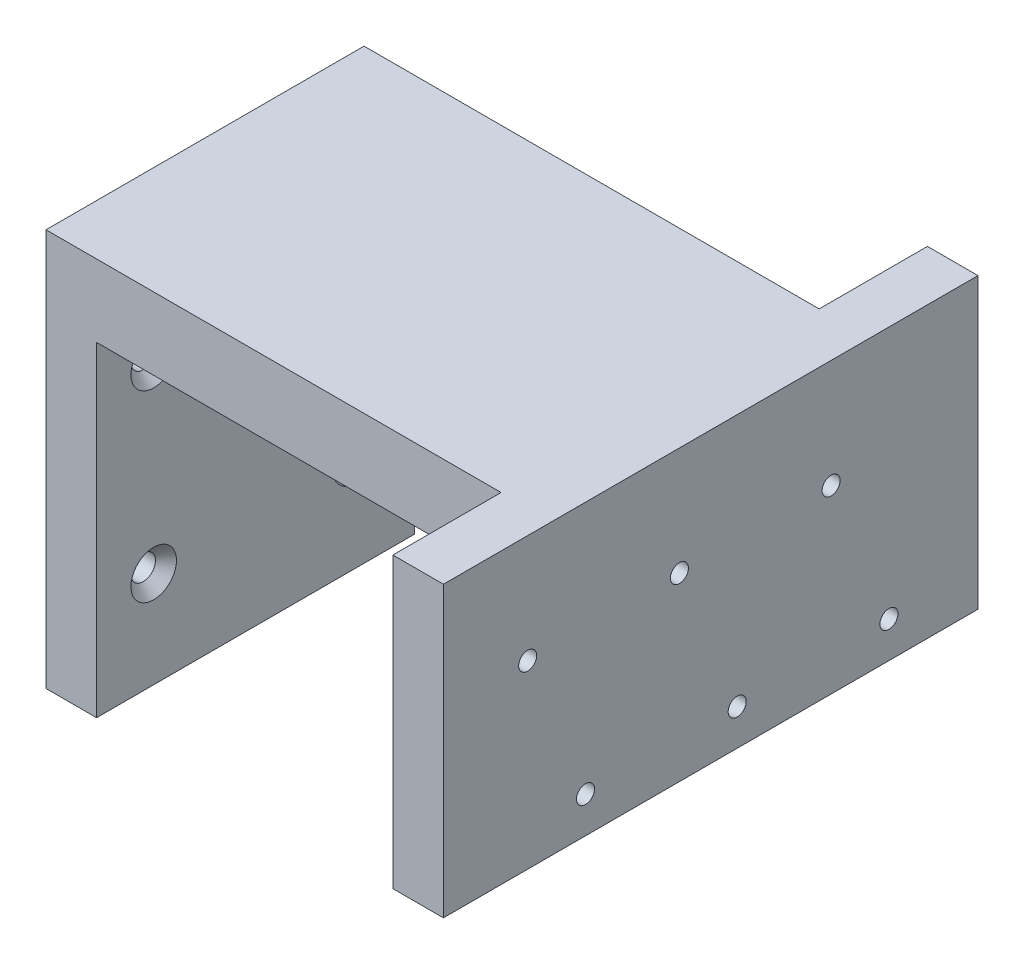
SolidWorks part; units mm, degrees
ref_plane "Front Plane" through (0, 0, 0) normal (0, 0, 1) x (1, 0, 0)
ref_plane "Top Plane" through (0, 0, 0) normal (0, 1, 0) x (1, 0, 0)
ref_plane "Right Plane" through (0, 0, 0) normal (1, 0, 0) x (0, 0, -1)
sketch "Sketch1" plane through (0, 0, 0) normal (0, 0, 1) x (1, 0, 0)
  line L1 (0, 0) -> (70, 0)
  line L2 (0, 0) -> (0, 55)
  line L3 (0, 55) -> (70, 55)
  line L4 (70, 0) -> (70, 55)
  dimension "D1" = 70
  dimension "D2" = 55
extrude "Boss-Extrude1" add sketch "Sketch1" along normal blind 74
sketch "Sketch2" plane through (0, 0, 74) normal (0, 0, 1) x (1, 0, 0)
  line L0 (7, 0) -> (7, 45)
  line L1 (0, 0) -> (70, 0) construction
  line L2 (7, 45) -> (63, 45)
  line L3 (63, 45) -> (63, 15)
  line L4 (60, 0) -> (7, 0)
  line L5 (0, 55) -> (0, 0) construction
  line L6 (70, 0) -> (70, 55) construction
  line L7 (70, 55) -> (0, 55) construction
  line L8 (63, 15) -> (70, 15)
  line L9 (70, 15) -> (70, 0)
  line L10 (70, 0) -> (60, 0)
  dimension "D1" = 7
  dimension "D2" = 7
  dimension "D3" = 10
  dimension "D4" = 15
extrude "Cut-Extrude1" cut sketch "Sketch2" against normal through all both and the other way through all
sketch "Sketch4" plane through (70, 0, 0) normal (1, 0, 0) x (0, 0, -1)
  line L0 (0, 15) -> (-74, 15) construction
  circle A0 centre (-83.3318, 40) radius 1.25
  circle A1 centre (-75.3318, 20) radius 1.25
  circle A2 centre (-62.3318, 40) radius 1.25
  circle A3 centre (-54.3318, 20) radius 1.25
  circle A4 centre (-41.3318, 40) radius 1.25
  circle A5 centre (-33.3318, 20) radius 1.25
  circle A6 centre (-20.3318, 40) radius 1.25
  circle A7 centre (-12.3318, 20) radius 1.25
  dimension "D1" = 2.5
  dimension "D2" = 2.5
  dimension "D5" = 2.5
  dimension "D6" = 2.5
  dimension "D10" = 2.5
  dimension "D11" = 2.5
  dimension "D14" = 2.5
  dimension "D15" = 2.5
  dimension "D3" = 8
  dimension "D4" = 20
  dimension "D7" = 8
  dimension "D8" = 20
  dimension "D9" = 13
  dimension "D12" = 8
  dimension "D13" = 20
  dimension "D16" = 8
  dimension "D17" = 20
  dimension "D18" = 13
  dimension "D19" = 13
  dimension "D20" = 5
  dimension "D21" = 5
  dimension "D22" = 5
  dimension "D23" = 5
extrude "Cut-Extrude4" cut sketch "Sketch4" against normal up to surface (7 mm away) up to face at (63, 30, 37)
sketch "Sketch5" plane through (0, 0, 0) normal (-1, 0, 0) x (0, 0, 1)
  line L0 (0, 27.5) -> (74, 27.5) construction
  line L1 (0, 55) -> (0, 0) construction
  line L2 (74, 55) -> (74, 0) construction
  line L3 (74, 0) -> (0, 0) construction
  line L4 (14.9857, 55) -> (59.0143, 55)
  line L5 (14.9857, 55) -> (14.9857, 0)
  line L6 (14.9857, 0) -> (59.0143, 0)
  line L7 (59.0143, 55) -> (59.0143, 0)
  line L8 (14.9857, 55) -> (59.0143, 0) construction
  line L9 (14.9857, 0) -> (59.0143, 55) construction
  line L11 (0, 55) -> (14.9857, 55)
  line L12 (0, 55) -> (0, 0)
  line L13 (0, 0) -> (14.9857, 0)
  line L14 (14.9857, 55) -> (14.9857, 0)
  line L15 (59.0143, 55) -> (74, 55)
  line L16 (59.0143, 55) -> (59.0143, 0)
  line L17 (59.0143, 0) -> (74, 0)
  line L18 (74, 55) -> (74, 0)
  point P6 (37, 27.5)
  line M2 (0, 55) -> (0, 0)
  line M3 (0, 0) -> (74, 0)
  line M4 (74, 0) -> (74, 55)
  line M5 (74, 55) -> (0, 55)
extrude "Cut-Extrude5" cut sketch "Sketch5" against normal blind 63 contours L5 M5 M2 M3 | L7 M5 M3 M4
sketch "Sketch8" plane through (7, 0, 0) normal (1, 0, 0) x (0, 0, 1)
  line L0 (37.1377, -10.1906) -> (37.1377, -48.2906) construction
  line L3 (16.1827, -26.0393) -> (58.0927, -26.0393) construction
  line L6 (23.1677, -13.3393) -> (23.1677, -38.7393) construction
  line L7 (30.1527, -10.1906) -> (30.1527, -48.2906) construction
  line L8 (44.1227, -10.1906) -> (44.1227, -48.2906) construction
  line L15 (58.0927, -10.1906) -> (16.1827, -10.1906) construction
  line L16 (16.1827, -10.1906) -> (16.1827, -48.2906) construction
  line L17 (16.1827, -48.2906) -> (58.0927, -48.2906) construction
  line L18 (58.0927, -48.2906) -> (58.0927, -10.1906) construction
  circle A0 centre (23.1677, -13.3393) radius 1
  circle A1 centre (51.1077, -13.3393) radius 1
  circle A2 centre (23.1677, -38.7393) radius 1
  circle A3 centre (51.1077, -38.7393) radius 1
  circle A4 centre (37.1377, -29.2406) radius 1
  point P0 (23.1677, -13.3393)
  point P2 (51.1077, -13.3393)
  point P4 (23.1677, -38.7393)
  point P6 (51.1077, -38.7393)
  point P10 (0, 0)
  point P32 (23.1677, -13.3393)
  point P39 (23.1677, -38.7393)
  dimension "D3" = 2
  dimension "D4" = 2
  dimension "D1" = 27.94
  dimension "D2" = 25.4
hole_wizard "CSK for M3 Countersunk Flat Head Screw1" positions "Sketch8" profile "Sketch9" countersink size "M3" standard "ISO"
sketch "Sketch9" plane through (7, 38.7393, 23.1677) normal (0, 1, 0) x (0, 0, -1)
  line L0 (0, 0) -> (0, 11.0215)
  line L1 (0, 11.0215) -> (1.7, 10)
  line L2 (1.7, 10) -> (1.7, 1.45)
  line L3 (1.7, 1.45) -> (3.15, 0)
  line L5 (3.15, 0) -> (0, 0)
  line L6 (-1.7, 1.45) -> (-3.15, 0) construction
  line L10 (0, 11.0215) -> (-1.7, 10) construction
  line L11 (0, -6.35) -> (0, 107.95) construction
  dimension "Hole Dia." = 3.4
  dimension "Hole Depth" = 10
  dimension "Near C'Sink Dia." = 6.3
  dimension "Near C'Sink Angle" = 90
  dimension "Drill Angle" = 118
